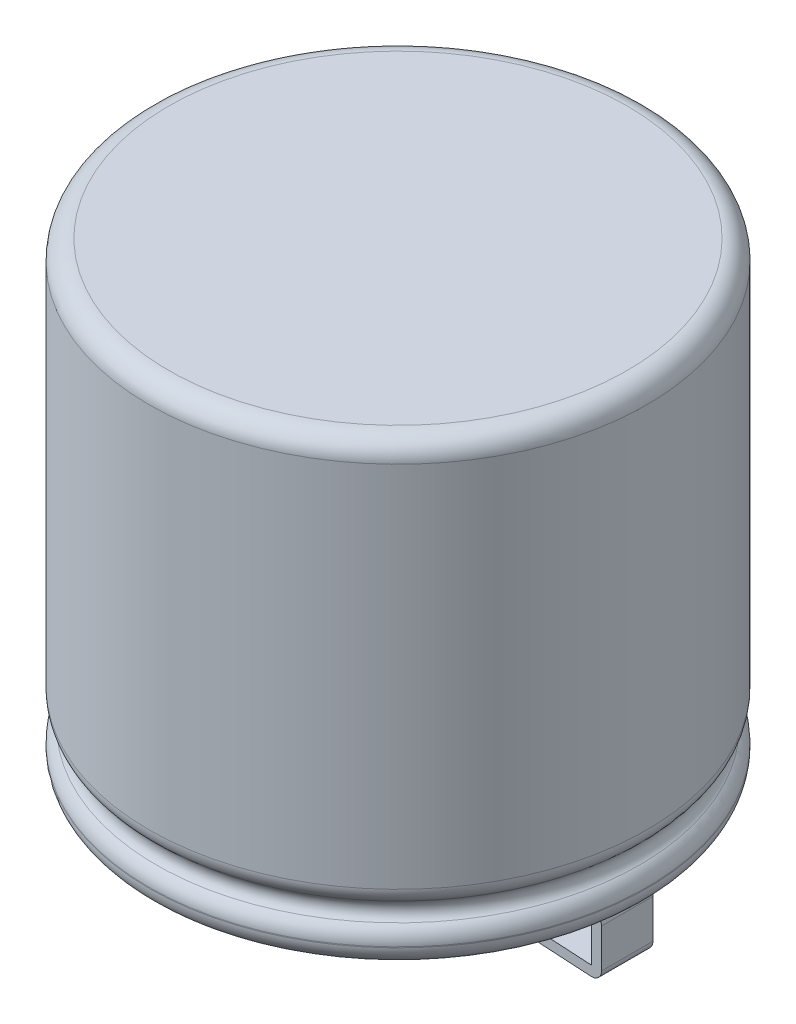
SolidWorks part; units mm, degrees
ref_plane "Front Plane" through (0, 0, 0) normal (0, 0, 1) x (1, 0, 0)
ref_plane "Top Plane" through (0, 0, 0) normal (0, 1, 0) x (1, 0, 0)
ref_plane "Right Plane" through (0, 0, 0) normal (1, 0, 0) x (0, 0, -1)
sketch "Sketch1" plane through (0, 0, 0) normal (1, 0, 0) x (0, 0, -1)
  line L0 (0, -4.5841) -> (0, 4.2459) construction
  line L1 (0, 2.9) -> (0, -2.9)
  line L2 (0, 2.9) -> (2.9, 2.9)
  line L3 (3.15, 2.65) -> (3.15, -2.0081)
  line L4 (3.15, -2.6383) -> (3.15, -2.65)
  line L5 (2.9, -2.9) -> (0, -2.9)
  arc A0 (3.0554, -2.204) -> (3.0554, -2.4424) centre (3.15, -2.3232) ccw
  arc A1 (3.15, -2.0081) -> (3.0554, -2.204) centre (2.9, -2.0081) cw
  arc A2 (3.0554, -2.4424) -> (3.15, -2.6383) centre (2.9, -2.6383) cw
  arc A3 (3.15, -2.65) -> (2.9, -2.9) centre (2.9, -2.65) cw
  arc A4 (2.9, 2.9) -> (3.15, 2.65) centre (2.9, 2.65) cw
  point P6 (0, 0)
  point P13 (3.15, -2.171)
  point P16 (3.15, -2.4754)
  dimension "D3" = 0.25
  dimension "D1" = 0.4246
  dimension "L" = 5.8
  dimension "D" = 6.3
  dimension "D2" = 0.729
revolve "Cap Body" add sketch "Sketch1" angle 360 about L0
sketch "Sketch2"
sketch "Tab Sketch" plane through (0, 0, 0) normal (0, 0, 1) x (1, 0, 0)
  line L0 (-0.7875, -2.9) -> (-2.775, -2.9)
  line L1 (-2.9, -2.9) -> (2.9, -2.9) construction
  line L2 (-2.9, -3.025) -> (-2.9, -3.5174)
  line L3 (-2.7676, -3.6422) -> (-0.7838, -3.5249)
  line L4 (0.7875, -2.9) -> (2.775, -2.9)
  line L5 (2.9, -3.025) -> (2.9, -3.5174)
  line L6 (2.7676, -3.6422) -> (0.7838, -3.5249)
  line L7 (-0.7875, -2.9) -> (0.7875, -2.9) construction
  line L8 (-0.7875, -3.025) -> (-2.775, -3.025)
  line L9 (-2.775, -3.025) -> (-2.775, -3.5174)
  line L10 (-2.775, -3.5174) -> (-0.7912, -3.4001)
  line L11 (0.7875, -3.025) -> (2.775, -3.025)
  line L12 (2.775, -3.025) -> (2.775, -3.5174)
  line L13 (2.775, -3.5174) -> (0.7912, -3.4001)
  arc A0 (2.775, -2.9) -> (2.9, -3.025) centre (2.775, -3.025) cw
  arc A1 (-2.775, -2.9) -> (-2.9, -3.025) centre (-2.775, -3.025) ccw
  arc A2 (2.9, -3.5174) -> (2.7676, -3.6422) centre (2.775, -3.5174) cw
  arc A3 (-2.9, -3.5174) -> (-2.7676, -3.6422) centre (-2.775, -3.5174) ccw
  arc A4 (-2.775, -3.025) -> (-2.775, -3.025) centre (-2.775, -3.025) ccw
  arc A5 (-2.775, -3.5174) -> (-2.775, -3.5174) centre (-2.775, -3.5174) ccw
  arc A6 (-0.7875, -2.9) -> (-0.7875, -3.025) centre (-0.7875, -2.9625) cw
  arc A7 (-0.7838, -3.5249) -> (-0.7912, -3.4001) centre (-0.7875, -3.4625) ccw
  arc A8 (2.775, -3.025) -> (2.775, -3.025) centre (2.775, -3.025) cw
  arc A9 (2.775, -3.5174) -> (2.775, -3.5174) centre (2.775, -3.5174) cw
  arc A10 (0.7875, -2.9) -> (0.7875, -3.025) centre (0.7875, -2.9625) ccw
  arc A11 (0.7838, -3.5249) -> (0.7912, -3.4001) centre (0.7875, -3.4625) cw
  point P10 (0, -2.9)
  point P16 (2.9, -2.9)
  point P19 (-2.9, -2.9)
  point P22 (2.9, -3.65)
  point P25 (-2.9, -3.65)
  dimension "D2" = 0.125
  dimension "D1" = 0.5
  dimension "Tab Height" = 0.75
  dimension "Tab Distance" = 1.575
  dimension "D3" = 0.125
  dimension "D4" = 0.125
  dimension "D5" = 0.5
extrude "Tab" add sketch "Tab Sketch" along normal mid plane 0.65 separate body
sketch "Sketch4" plane through (0, -2.9, 0) normal (0, -1, 0) x (1, 0, 0)
  line L0 (3.15, 0) -> (-3.15, 0) construction
  line L1 (-0.725, -0.325) -> (-0.725, 0.325) construction
  line L2 (-2.7676, 0.325) -> (-0.7838, 0.325) construction
  line L3 (0.725, 0.325) -> (0.725, -0.325) construction
  line L4 (0.7838, 0.325) -> (2.7676, 0.325) construction
  line L5 (-1.05, 0.325) -> (-0.725, 0.325)
  line L7 (-0.725, -0.325) -> (-1.05, -0.325)
  line L8 (1.05, 0.325) -> (0.725, 0.325)
  line L10 (0.725, -0.325) -> (1.05, -0.325)
  line L11 (-0.725, 0.325) -> (0.725, 0.325)
  line L12 (-0.725, -0.325) -> (0.725, -0.325)
  circle A0 centre (0, 0) radius 3.15 construction
  arc A1 (-1.05, -0.325) -> (-1.05, 0.325) centre (-1.05, 0) ccw
  arc A2 (1.05, 0.325) -> (1.05, -0.325) centre (1.05, 0) ccw
  point P7 (0, 0)
extrude "Cut-Extrude1" cut sketch "Sketch4" along normal through all
equation "\"D1@Tab\"=\"tab width@6.3V 10uf\""
